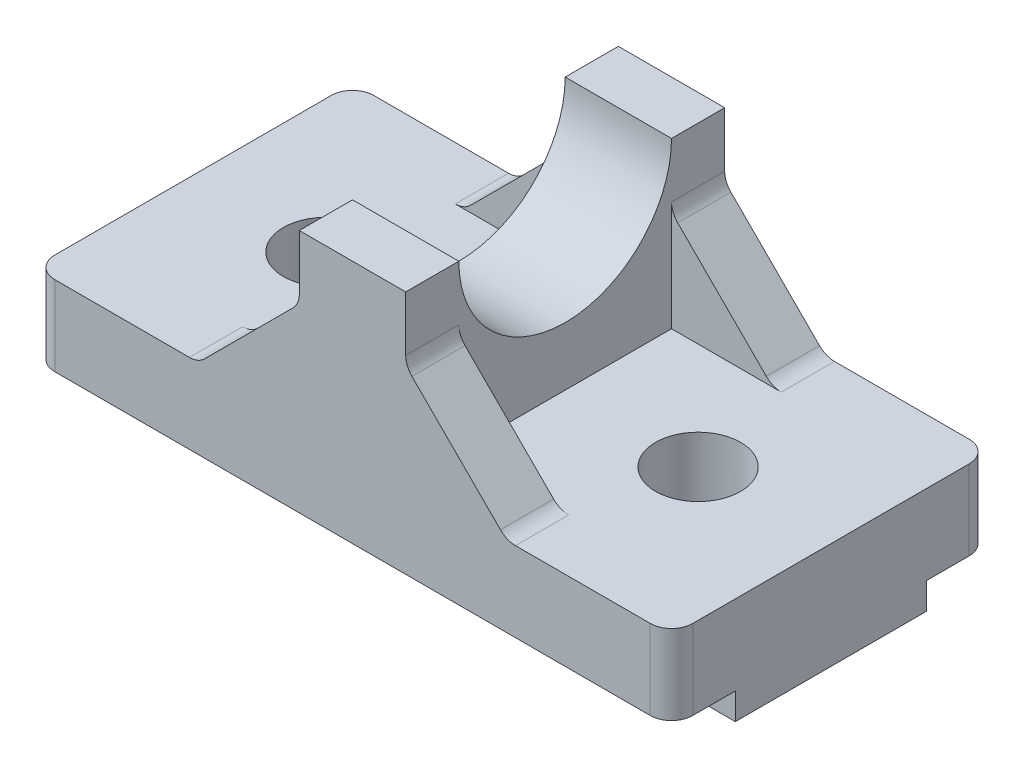
SolidWorks part; units mm, degrees
ref_plane "Front Plane" through (0, 0, 0) normal (0, 0, 1) x (1, 0, 0)
ref_plane "Top Plane" through (0, 0, 0) normal (0, 1, 0) x (1, 0, 0)
ref_plane "Right Plane" through (0, 0, 0) normal (1, 0, 0) x (0, 0, -1)
sketch "Sketch1" plane through (0, 0, 0) normal (0, 0, 1) x (1, 0, 0)
  line L1 (10, 46) -> (-10, 46)
  line L2 (-10, 46) -> (-10, 35.6569)
  line L3 (-11.1716, 32.8284) -> (-27.8284, 16.1716)
  line L4 (-30.6569, 15) -> (-60, 15)
  line L5 (-60, 15) -> (-60, 0)
  line L6 (-60, 0) -> (60, 0)
  line L7 (60, 15) -> (60, 0)
  line L8 (30.6569, 15) -> (60, 15)
  line L9 (11.1716, 32.8284) -> (27.8284, 16.1716)
  line L10 (10, 46) -> (10, 35.6569)
  arc A0 (-27.8284, 16.1716) -> (-30.6569, 15) centre (-30.6569, 19) cw
  arc A1 (-10, 35.6569) -> (-11.1716, 32.8284) centre (-14, 35.6569) cw
  arc A2 (10, 35.6569) -> (11.1716, 32.8284) centre (14, 35.6569) ccw
  arc A3 (27.8284, 16.1716) -> (30.6569, 15) centre (30.6569, 19) ccw
  point P12 (-10, 34)
  point P22 (10, 34)
  dimension "D7" = 4
  dimension "D3" = 15
  dimension "D6" = 12
extrude "Boss-Extrude1" add sketch "Sketch1" along normal mid plane 60
sketch "Sketch2" plane through (0, 0, 0) normal (1, 0, 0) x (0, 0, -1)
  line L0 (-30, 0) -> (30, 0) construction
  line L1 (-18, -5) -> (18, -5)
  line L2 (-18, -5) -> (-18, 0)
  line L3 (-18, 0) -> (18, 0)
  line L4 (18, -5) -> (18, 0)
  line L5 (-18, -5) -> (18, 0) construction
  line L6 (-18, 0) -> (18, -5) construction
  point P0 (0, -2.5)
  point P7 (0, 0)
  dimension "D1" = 5
  dimension "D2" = 36
extrude "Boss-Extrude2" add sketch "Sketch2" along normal mid plane 120
fillet "Fillet1" radius 4 4 edges at (-60, 7.5, -30) (60, 7.5, -30) (60, 7.5, 30) (-60, 7.5, 30)
sketch "Sketch4" plane through (0, 46, 0) normal (0, 1, 0) x (1, 0, 0)
  line L0 (-10, -30) -> (-10, 30) construction
  line L1 (-10, 20) -> (-30.6569, 20)
  line L2 (-10, 20) -> (-10, -20)
  line L3 (-10, -20) -> (-30.6569, -20)
  line L4 (-30.6569, 20) -> (-30.6569, -20)
  line L5 (-30.6569, -30) -> (-30.6569, 30) construction
  line L6 (-11.1716, 30) -> (-27.8284, 30) construction
  point P8 (-10, 0)
  dimension "D1" = 10
extrude "Cut-Extrude1" cut sketch "Sketch4" against normal blind 31
sketch "Sketch3" plane through (0, 15, 0) normal (0, 1, 0) x (1, 0, 0)
  line L0 (-30.6569, 30) -> (-56, 30) construction
  line L2 (-60, -26) -> (-60, 26) construction
  circle A0 centre (-35, 0) radius 8
  point P6 (-60, -4.26)
  point P7 (0, 0)
  point P8 (0, 0)
  dimension "D3" = 16
  dimension "D1" = 30
  dimension "D2" = 25
extrude "Cut-Extrude2" cut sketch "Sketch3" against normal up to next contours A0
mirror "Mirror1" about plane through (0, 0, 0) normal (1, 0, 0) of "Cut-Extrude1", "Cut-Extrude2"
sketch "Sketch5" plane through (-10, 0, 0) normal (-1, 0, 0) x (0, 0, 1)
  line L0 (30, 46) -> (-30, 46) construction
  arc A0 (-20, 46) -> (20, 46) centre (0, 46) ccw
  point P3 (0, 0)
  point P7 (0, 0)
  dimension "D1" = 20
extrude "Cut-Extrude3" cut sketch "Sketch5" against normal through all and the other way through all
